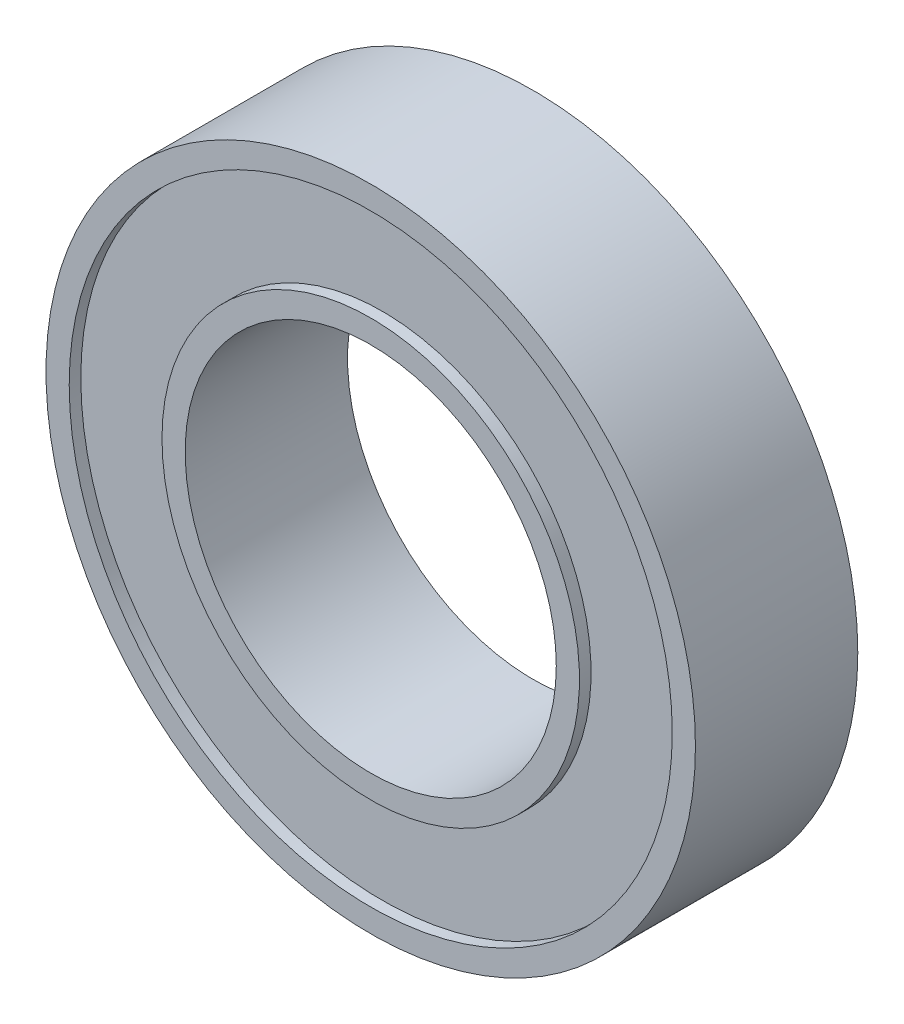
SolidWorks part; units mm, degrees
ref_plane "Front Plane" through (0, 0, 0) normal (0, 0, 1) x (1, 0, 0)
ref_plane "Top Plane" through (0, 0, 0) normal (0, 1, 0) x (1, 0, 0)
ref_plane "Right Plane" through (0, 0, 0) normal (1, 0, 0) x (0, 0, -1)
sketch "Sketch1" plane through (0, 0, 0) normal (0, 0, 1) x (1, 0, 0)
  circle A0 centre (0, 0) radius 8
  circle A1 centre (0, 0) radius 14
  dimension "D1" = 16
  dimension "D2" = 28
extrude "Boss-Extrude1" add sketch "Sketch1" along normal mid plane 7
sketch "Sketch2" plane through (0, 0, 3.5) normal (0, 0, 1) x (1, 0, 0)
  circle A2 centre (0, 0) radius 9
  circle A3 centre (0, 0) radius 9
  circle A5 centre (0, 0) radius 13
  circle A6 centre (0, 0) radius 13
  dimension "D1" = 1
  dimension "D2" = 1
extrude "Cut-Extrude1" cut sketch "Sketch2" against normal blind 0.5 and the other way through all
mirror "Mirror1" about plane through (0, 0, 0) normal (0, 0, 1) of "Cut-Extrude1" second plane through (0, 0, 0) second plane normal (1, 0, 0)
